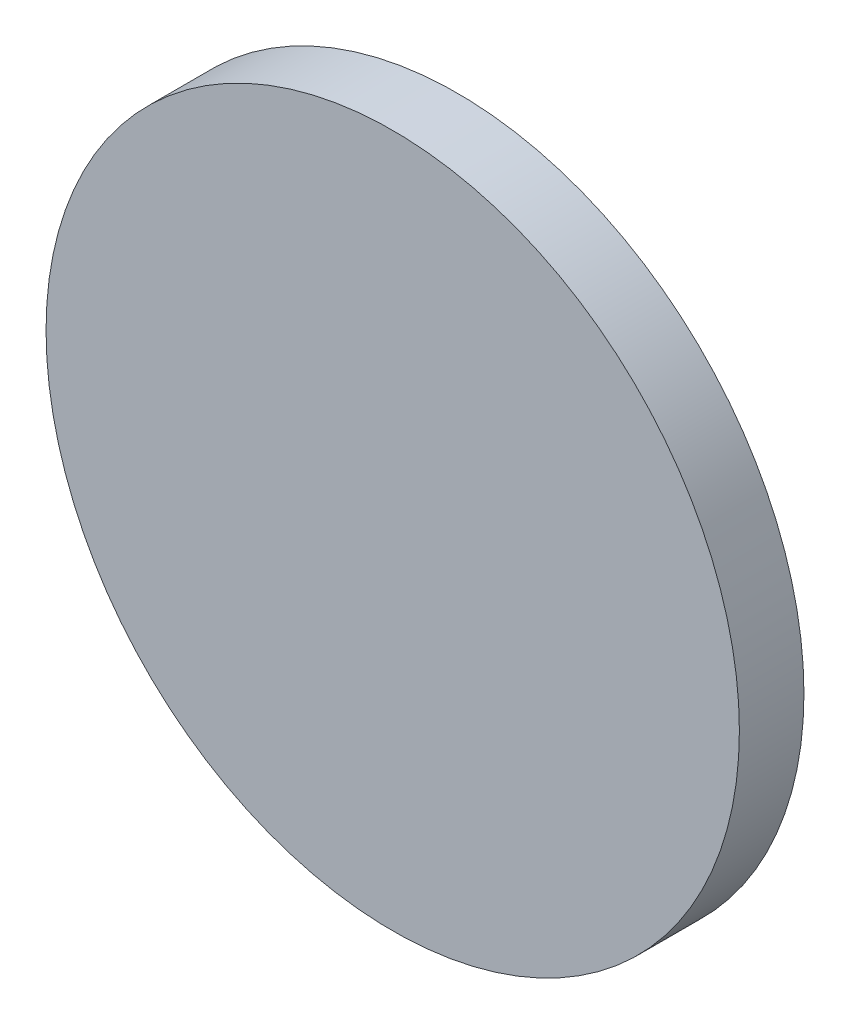
SolidWorks part; units mm, degrees
ref_plane "Front Plane" through (0, 0, 0) normal (0, 0, 1) x (1, 0, 0)
ref_plane "Top Plane" through (0, 0, 0) normal (0, 1, 0) x (1, 0, 0)
ref_plane "Right Plane" through (0, 0, 0) normal (1, 0, 0) x (0, 0, -1)
sketch "Sketch1" plane through (0, 0, 0) normal (0, 0, 1) x (1, 0, 0)
  circle A0 centre (0, 0) radius 53.6981
extrude "Boss-Extrude1" add sketch "Sketch1" along normal blind 10
